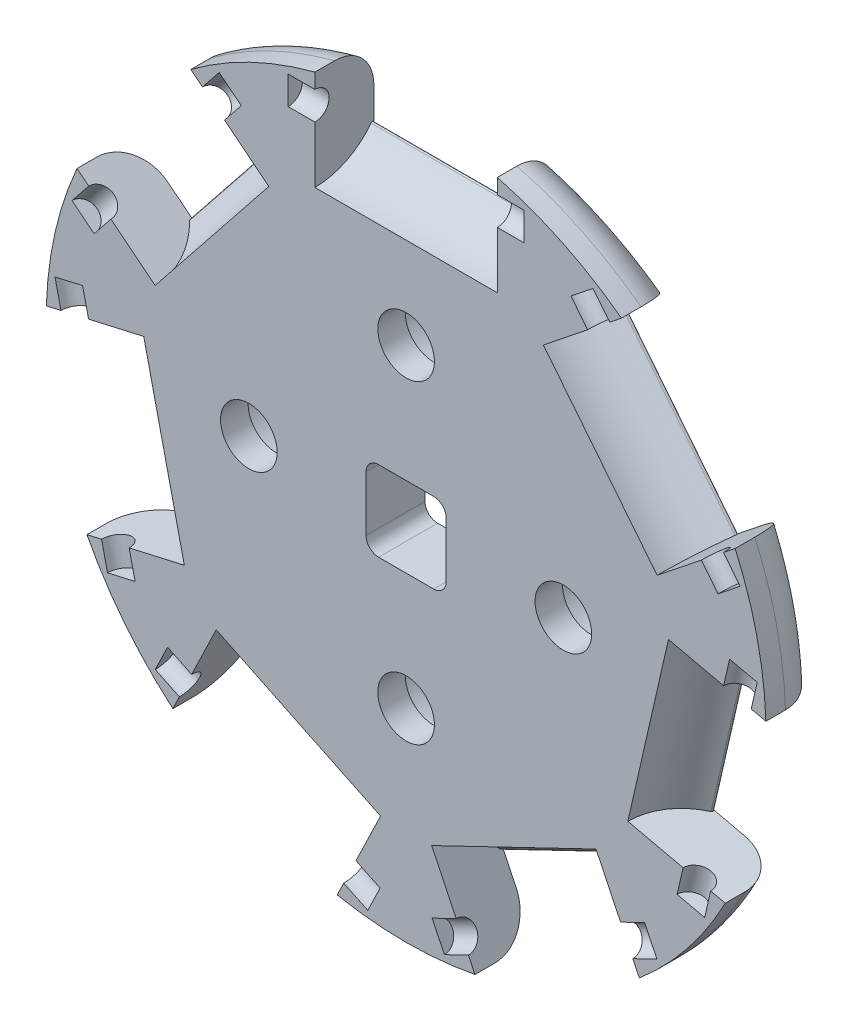
SolidWorks part; units mm, degrees
other "Markup1"
sketch "Sketch8" plane through (32.7336, 32.7336, 0) normal (0.5701, 0.1846, 0.8006) x (0.8043, 0.0736, -0.5897)
ref_plane "Front Plane" through (0, 0, 0) normal (0, 0, 1) x (1, 0, 0)
ref_plane "Top Plane" through (0, 0, 0) normal (0, 1, 0) x (1, 0, 0)
ref_plane "Right Plane" through (0, 0, 0) normal (1, 0, 0) x (0, 0, -1)
sketch "Sketch1" plane through (0, 0, 0) normal (0, 0, 1) x (1, 0, 0)
  circle A0 centre (0, 0) radius 29.0703
  dimension "D1" = 58.1406
extrude "Boss-Extrude2" add sketch "Sketch1" against normal blind 4.7625
fillet "Fillet1" radius 3.175 1 edges at (29.0703, 0, -4.7625)
sketch "Sketch2" plane through (0, 0, 0) normal (0, 0, 1) x (1, 0, 0)
  line L1 (-12.7, 29.0703) -> (12.7, 29.0703) construction
  line L2 (-7.366, 30.3403) -> (7.366, 30.3403)
  line L3 (-7.366, 30.3403) -> (-7.366, 19.9263)
  line L4 (-7.366, 19.9263) -> (7.366, 19.9263)
  line L5 (7.366, 30.3403) -> (7.366, 19.9263)
  line L6 (-7.366, 30.3403) -> (7.366, 19.9263) construction
  line L7 (-7.366, 19.9263) -> (7.366, 30.3403) construction
  line L35 (0, 0) -> (0, 29.0703) construction
  circle A1 centre (0, 0) radius 29.0703 construction
  point P10 (0, 25.1333)
  circle M7 centre (0, 0) radius 29.0703
  dimension "D1" = 14.732
  dimension "D2" = 10.414
  dimension "D3" = 1.27
  dimension "D4" = 25.4
extrude "Cut-Extrude2" cut sketch "Sketch2" against normal blind 12.7 contours L5 L3 L4 M7
pattern_circular "CirPattern1" count 7 over 360 about axis through (0, 0, 0) along (0, 0, 1) of "Cut-Extrude2"
ref_plane "Plane1" through (0, 0, 0) normal (1, 0, 0) x (0, 0, -1)
sketch "Sketch4" plane through (0, 0, 0) normal (1, 0, 0) x (0, 0, -1)
  line L0 (4.7625, 19.9263) -> (0, 19.9263) construction
  circle A0 centre (0, 25.7683) radius 1.143
  dimension "D1" = 2.286
  dimension "D2" = 5.842
extrude "Cut-Extrude4" cut sketch "Sketch4" against normal mid plane 19.05
pattern_circular "CirPattern2" count 7 over 360 about axis through (0, 0, 0) along (0, 0, 1) of "Cut-Extrude4"
sketch "Sketch5" plane through (0, 0, 0) normal (0, 0, 1) x (1, 0, 0)
  line L1 (-3.2385, -3.2385) -> (3.2385, -3.2385)
  line L2 (-3.2385, -3.2385) -> (-3.2385, 3.2385)
  line L3 (-3.2385, 3.2385) -> (3.2385, 3.2385)
  line L4 (3.2385, -3.2385) -> (3.2385, 3.2385)
  line L5 (-3.2385, -3.2385) -> (3.2385, 3.2385) construction
  line L6 (-3.2385, 3.2385) -> (3.2385, -3.2385) construction
  point P0 (0, 0)
  dimension "D1" = 6.477
extrude "Cut-Extrude5" cut sketch "Sketch5" against normal through all
sketch "Sketch6" plane through (0, 0, -4.7625) normal (0, 0, -1) x (-1, 0, 0)
  circle A1 centre (12.7, 0) radius 2.286
  circle A4 centre (0, -12.7) radius 2.286
  circle A5 centre (-12.7, 0) radius 2.286
  circle A6 centre (0, 12.7) radius 2.286
  point P12 (0, 0)
  dimension "D4" = 4.572
  dimension "D1" = 12.7
  dimension "D2" = 4
extrude "Cut-Extrude7" cut sketch "Sketch6" against normal through all
sketch "Sketch7" plane through (0, 0, -4.7625) normal (0, 0, -1) x (-1, 0, 0)
  circle A1 centre (12.7, 0) radius 4.445
  circle A4 centre (0, -12.7) radius 4.445
  circle A5 centre (-12.7, 0) radius 4.445
  circle A6 centre (0, 12.7) radius 4.445
  point P15 (0, 0)
  dimension "D1" = 4
  dimension "D2" = 8.89
extrude "Cut-Extrude8" cut sketch "Sketch7" against normal blind 2.54
sketch "Sketch10" plane through (7.366, 0, 0) normal (-1, 0, 0) x (0, 0, 1)
  line L0 (-4.7625, 24.8256) -> (-4.7625, 19.9263) construction
  line L1 (-4.7625, 19.9263) -> (0, 19.9263)
  line L2 (-4.7625, 19.9263) -> (-4.7625, 22.6092)
  line L4 (0, 19.9263) -> (0, 20.0533)
  arc A0 (-4.7625, 22.6092) -> (0, 20.0533) centre (0, 25.7683) ccw
  dimension "D1" = 11.43
  dimension "D2" = 4.7625
extrude "Boss-Extrude4" add sketch "Sketch10" along normal up to next
fillet "Fillet2" radius 0.127 1 edges at (0, 22.6092, -4.7625)
pattern_circular "CirPattern5" count 7 over 360 about axis through (0, 0, 0) along (0, 0, 1) of "Boss-Extrude4", "Fillet2"
fillet "Fillet3" radius 1.016 4 edges at (3.2385, -3.2385, -2.3813) (3.2385, 3.2385, -2.3813) (-3.2385, 3.2385, -2.3813) (-3.2385, -3.2385, -2.3813)
